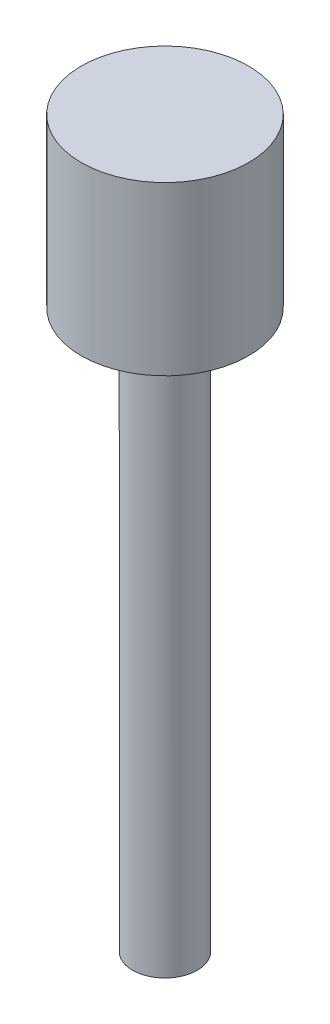
SolidWorks part; units mm, degrees
ref_plane "CL Y" through (0, 0, 0) normal (0, 0, 1) x (1, 0, 0)
ref_plane "Bottom" through (0, 0, 0) normal (0, 1, 0) x (1, 0, 0)
ref_plane "CL X" through (0, 0, 0) normal (1, 0, 0) x (0, 0, -1)
sketch "Sketch1" plane through (0, 0, 0) normal (0, 1, 0) x (1, 0, 0)
  circle A0 centre (0, 0) radius 7.5
  dimension "D1" = 15
extrude "Boss-Extrude1" add sketch "Sketch1" against normal blind 15
sketch "Sketch3" plane through (0, -15, 0) normal (0, -1, 0) x (1, 0, 0)
  circle A0 centre (0, 0) radius 2.9
  dimension "D1" = 5.8
extrude "Boss-Extrude3" add sketch "Sketch3" along normal blind 50
sketch "Sketch4" plane through (0, -65, 0) normal (0, 1, 0) x (1, 0, 0)
  circle A0 centre (0, 0) radius 1.65
  dimension "D1" = 3.3
extrude "Cut-Extrude1" cut sketch "Sketch4" along normal blind 12
